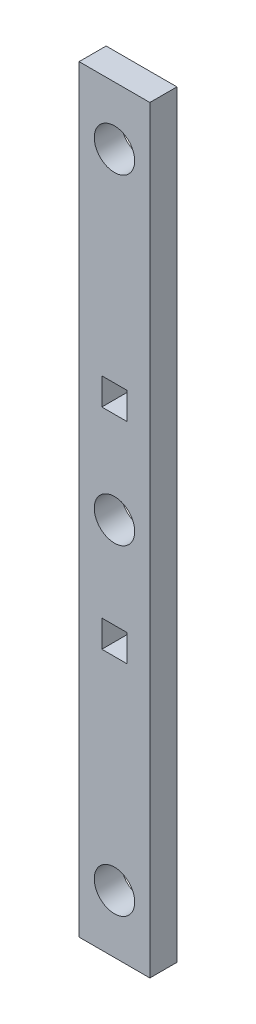
SolidWorks part; units mm, degrees
ref_plane "Front Plane" through (0, 0, 0) normal (0, 0, 1) x (1, 0, 0)
ref_plane "Top Plane" through (0, 0, 0) normal (0, 1, 0) x (1, 0, 0)
ref_plane "Right Plane" through (0, 0, 0) normal (1, 0, 0) x (0, 0, -1)
sketch "Model" plane through (0, 0, 0) normal (0, 0, 1) x (1, 0, 0)
  line L56 (9.5, 56.925) -> (4.5, 56.925)
  line L57 (4.5, 56.925) -> (4.5, 51.575)
  line L58 (4.5, 51.575) -> (9.5, 51.575)
  line L59 (9.5, 51.575) -> (9.5, 56.925)
  line L60 (0, 150) -> (0, 0)
  line L61 (14, 150) -> (0, 150)
  line L62 (14, 0) -> (14, 150)
  line L63 (0, 0) -> (14, 0)
  line L64 (4.5, 93.075) -> (9.5, 93.075)
  line L65 (9.5, 93.075) -> (9.5, 98.425)
  line L66 (9.5, 98.425) -> (4.5, 98.425)
  line L67 (4.5, 98.425) -> (4.5, 93.075)
  circle A2 centre (7, 75) radius 4
  circle A3 centre (7, 11.5) radius 4
  circle A4 centre (7, 138.5) radius 4
extrude "Boss-Extrude1" add sketch "Model" along normal blind 5.35
